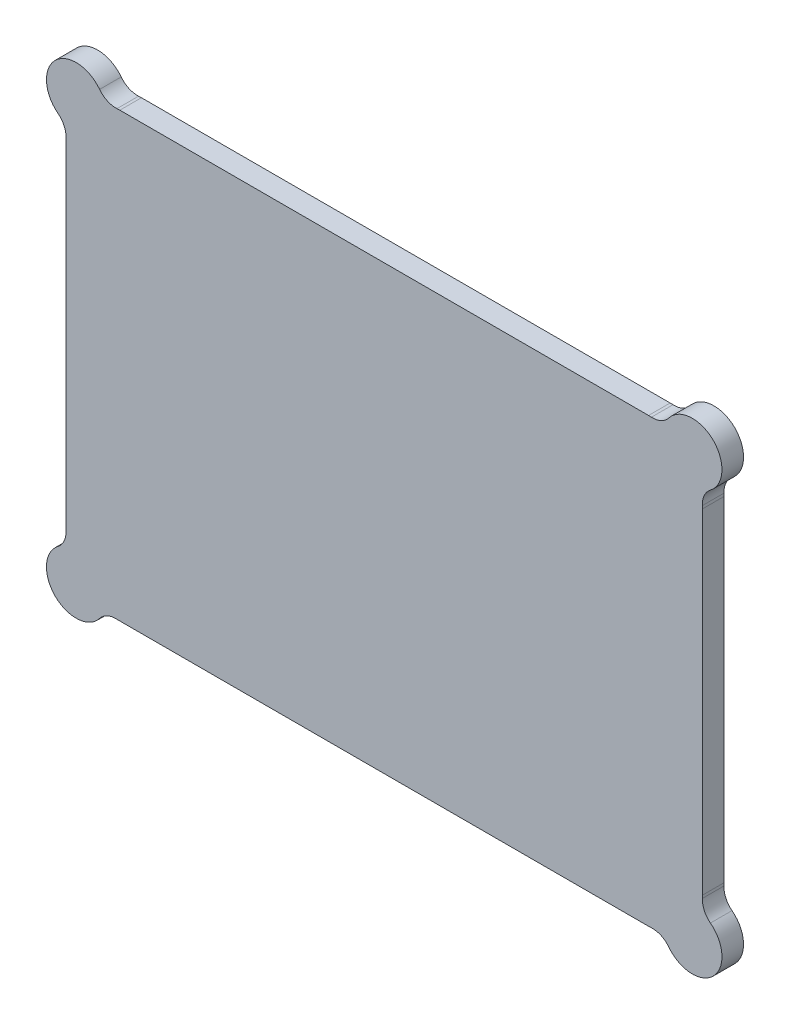
SolidWorks part; units mm, degrees
material "Custom Plastic"
ref_plane "X-Y Datum" through (0, 0, 0) normal (0, 0, 1) x (1, 0, 0)
ref_plane "X-Z Datum" through (0, 0, 0) normal (0, 1, 0) x (1, 0, 0)
ref_plane "Y-Z Datum" through (0, 0, 0) normal (1, 0, 0) x (0, 0, -1)
sketch "Sketch2" plane through (0, 0, 0) normal (0, 0, 1) x (1, 0, 0)
  line L4 (59, 41) -> (-59, 41)
  line L6 (59, 41) -> (-59, 41)
  line L20 (-60.27, -41) -> (60.27, -41)
  line L21 (-60.27, -41) -> (60.27, -41)
  line L22 (59, 40.8514) -> (59, 41)
  line L23 (59, 40.8514) -> (59, 41)
  line L33 (-59, 41) -> (-59, 40.8514)
  line L34 (-59, 41) -> (-59, 40.8514)
  line L35 (-59, 27.6986) -> (-59, -27.6986)
  line L36 (-59, 27.6986) -> (-59, -27.6986)
  line L37 (59, -27.6986) -> (59, 27.6986)
  line L39 (59, -27.6986) -> (59, 27.6986)
  line L57 (-59, 31) -> (-59, -31)
  line L61 (-49, -41) -> (49, -41)
  line L65 (59, -31) -> (59, 31)
  line L66 (49, 41) -> (-49, 41)
  arc A4 (61.0447, 30.0548) -> (59, 40.8514) centre (60.27, 35.5) ccw
  arc A12 (61.0447, 30.0548) -> (59, 40.8514) centre (60.27, 35.5) ccw
  arc A14 (-59, 40.8514) -> (-61.0447, 30.0548) centre (-60.27, 35.5) ccw
  arc A26 (-59, 40.8514) -> (-61.0447, 30.0548) centre (-60.27, 35.5) ccw
  arc A27 (-59, 27.6986) -> (-61.0447, 30.0548) centre (-61.38, 27.6986) ccw
  arc A29 (-59, 27.6986) -> (-61.0447, 30.0548) centre (-61.38, 27.6986) ccw
  arc A31 (-61.0447, -30.0548) -> (-59, -27.6986) centre (-61.38, -27.6986) ccw
  arc A32 (-61.0447, -30.0548) -> (-59, -27.6986) centre (-61.38, -27.6986) ccw
  arc A33 (-61.0447, -30.0548) -> (-60.27, -41) centre (-60.27, -35.5) ccw
  arc A34 (-61.0447, -30.0548) -> (-60.27, -41) centre (-60.27, -35.5) ccw
  arc A35 (60.27, -41) -> (61.0447, -30.0548) centre (60.27, -35.5) ccw
  arc A36 (60.27, -41) -> (61.0447, -30.0548) centre (60.27, -35.5) ccw
  arc A37 (59, -27.6986) -> (61.0447, -30.0548) centre (61.38, -27.6986) ccw
  arc A38 (59, -27.6986) -> (61.0447, -30.0548) centre (61.38, -27.6986) ccw
  arc A39 (61.0447, 30.0548) -> (59, 27.6986) centre (61.38, 27.6986) ccw
  arc A40 (61.0447, 30.0548) -> (59, 27.6986) centre (61.38, 27.6986) ccw
  arc A96 (-59, -31) -> (-58.9859, -31.5308) centre (-49, -31) ccw
  arc A97 (-60.4645, -34.7506) -> (-58.9859, -31.5308) centre (-62.7905, -31.7331) ccw
  arc A98 (-60.4645, -34.7506) -> (-52.7506, -42.4645) centre (-57.1066, -39.1066) ccw
  arc A99 (-49.5308, -40.9859) -> (-52.7506, -42.4645) centre (-49.7331, -44.7905) ccw
  arc A100 (-49.5308, -40.9859) -> (-49, -41) centre (-49, -31) ccw
  arc A101 (49, -41) -> (49.5308, -40.9859) centre (49, -31) ccw
  arc A102 (52.7506, -42.4645) -> (49.5308, -40.9859) centre (49.7331, -44.7905) ccw
  arc A103 (52.7506, -42.4645) -> (60.4645, -34.7506) centre (57.1066, -39.1066) ccw
  arc A104 (58.9859, -31.5308) -> (60.4645, -34.7506) centre (62.7905, -31.7331) ccw
  arc A105 (58.9859, -31.5308) -> (59, -31) centre (49, -31) ccw
  arc A106 (59, 31) -> (58.9859, 31.5308) centre (49, 31) ccw
  arc A107 (60.4645, 34.7506) -> (58.9859, 31.5308) centre (62.7905, 31.7331) ccw
  arc A108 (60.4645, 34.7506) -> (52.7506, 42.4645) centre (57.1066, 39.1066) ccw
  arc A109 (49.5308, 40.9859) -> (52.7506, 42.4645) centre (49.7331, 44.7905) ccw
  arc A110 (49.5308, 40.9859) -> (49, 41) centre (49, 31) ccw
  arc A111 (-49, 41) -> (-49.5308, 40.9859) centre (-49, 31) ccw
  arc A112 (-52.7506, 42.4645) -> (-49.5308, 40.9859) centre (-49.7331, 44.7905) ccw
  arc A113 (-52.7506, 42.4645) -> (-60.4645, 34.7506) centre (-57.1066, 39.1066) ccw
  arc A114 (-58.9859, 31.5308) -> (-60.4645, 34.7506) centre (-62.7905, 31.7331) ccw
  arc A115 (-58.9859, 31.5308) -> (-59, 31) centre (-49, 31) ccw
  dimension "D1" = 0
extrude "Boss-Extrude1" add sketch "Sketch2" along normal blind 4 contours L57 A96 A97 A98 A99 A100 L61 A101 A102 A103 A104 A105 L65 A106 A107 A108 A109 A110 L66 A111 A112 A113 A114 A115
